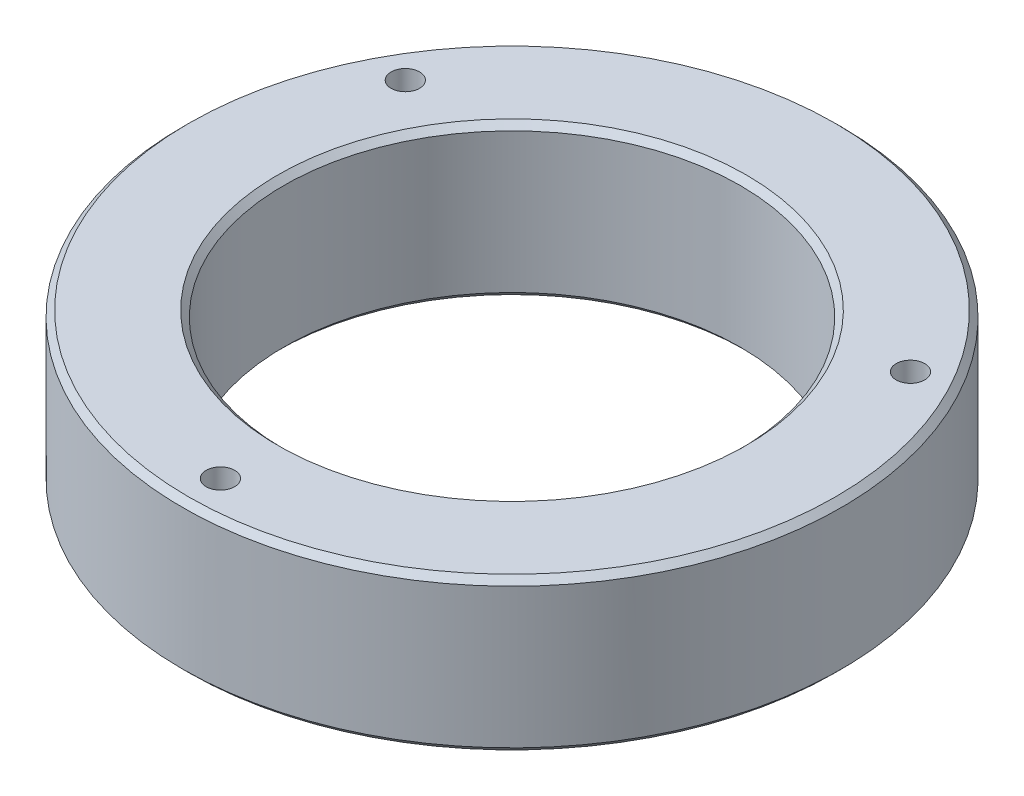
SolidWorks part; units mm, degrees
ref_plane "Front Plane" through (0, 0, 0) normal (1, 0, 0) x (0, 1, 0)
ref_plane "Top Plane" through (0, 0, 0) normal (0, 0, 1) x (0, 1, 0)
ref_plane "Right Plane" through (0, 0, 0) normal (0, 1, 0) x (-1, 0, 0)
sketch "Sketch1" plane through (0, 0, 0) normal (0, 0, 1) x (0, 1, 0)
  line L0 (-19.05, 82.5246) -> (19.05, 82.5246)
  line L1 (19.05, 82.5246) -> (19.05, 57.15)
  line L2 (19.05, 57.15) -> (-19.05, 57.15)
  line L3 (-19.05, 57.15) -> (-19.05, 82.5246)
  line L4 (-44.45, 0) -> (44.45, 0) construction
revolve "Revolve1" add sketch "Sketch1" angle 360 about L4
chamfer "Chamfer1" distance 1.524 angle 45 4 edges at (0, 19.05, -57.15) (0, -19.05, -57.15) (0, 19.05, -82.5246) (0, -19.05, -82.5246)
hole_wizard "CBORE for 1/4 Socket Head Cap Screw1" positions "Sketch3" profile "Sketch2" counterbore size "1/4" standard "ANSI Inch"
sketch "Sketch3" plane through (0, -19.05, 0) normal (0, -1, 0) x (-1, 0, 0)
  circle A0 centre (0, 0.0068) radius 73.0318 construction
  point P0 (0, -73.025)
  point P1 (-63.246, 36.5252)
  point P3 (63.246, 36.5252)
sketch "Sketch2" plane through (0, -19.05, 73.025) normal (1, 0, 0) x (0, 0, -1)
  line L0 (0, 0) -> (0, 40.2443)
  line L1 (0, 40.2443) -> (3.5687, 38.1)
  line L2 (3.5687, 38.1) -> (3.5687, 9.652)
  line L3 (3.5687, 9.652) -> (5.5626, 9.652)
  line L4 (5.5626, 9.652) -> (5.5626, 0)
  line L5 (5.5626, 0) -> (0, 0)
  line L10 (0, 40.2443) -> (-3.5687, 38.1) construction
  line L11 (0, -6.35) -> (0, 107.95) construction
  dimension "Hole Dia." = 7.1374
  dimension "Hole Depth" = 38.1
  dimension "C'Bore Dia." = 11.1252
  dimension "C'Bore Depth" = 9.652
  dimension "Drill Angle" = 118
hole_wizard "3/8-16 Tapped Hole2" positions "Sketch7" profile "Sketch6" tap size "3/8-16" standard "ANSI Inch"
sketch "Sketch7" plane through (0, -19.05, 0) normal (0, -1, 0) x (-1, 0, 0)
  point P0 (-69.85, 0)
  point P1 (69.85, 0)
sketch "Sketch6" plane through (69.85, -19.05, 0) normal (1, 0, 0) x (0, 0, -1)
  line L0 (0, 0) -> (0, 27.7847)
  line L1 (0, 27.7847) -> (3.9687, 25.4)
  line L2 (3.9687, 25.4) -> (3.9687, 0)
  line L5 (3.9687, 0) -> (0, 0)
  line L10 (0, 27.7847) -> (-3.9687, 25.4) construction
  line L11 (0, -6.35) -> (0, 107.95) construction
  dimension "Tap Drill Dia." = 7.9375
  dimension "Tap Drill Depth" = 25.4
  dimension "Drill Angle" = 118
cosmetic thread "Hole Thread3" parameters "D1"=19.05, "D2"=9.525
cosmetic thread "Hole Thread4" parameters "D1"=19.05, "D2"=9.525
